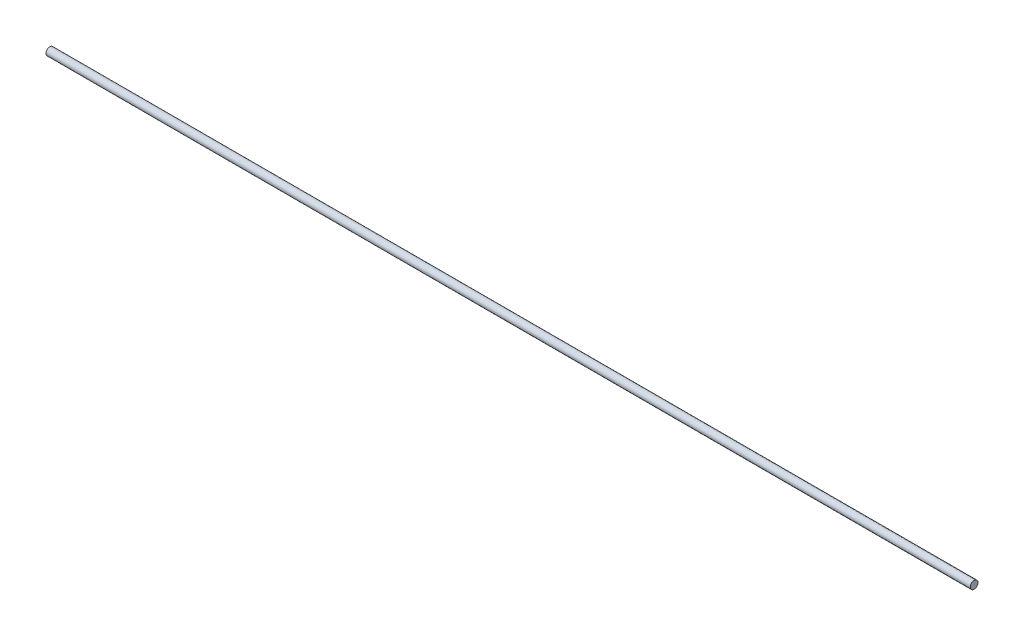
SolidWorks part; units mm, degrees
ref_plane "Front Plane" through (0, 0, 0) normal (0, 0, 1) x (1, 0, 0)
ref_plane "Top Plane" through (0, 0, 0) normal (0, 1, 0) x (1, 0, 0)
ref_plane "Right Plane" through (0, 0, 0) normal (1, 0, 0) x (0, 0, -1)
sketch "Sketch1" plane through (0, 0, 0) normal (1, 0, 0) x (0, 0, -1)
  circle A0 centre (0, 0) radius 6.35
  dimension "D1" = 12.7
extrude "Boss-Extrude1" add sketch "Sketch1" along normal blind 1524
